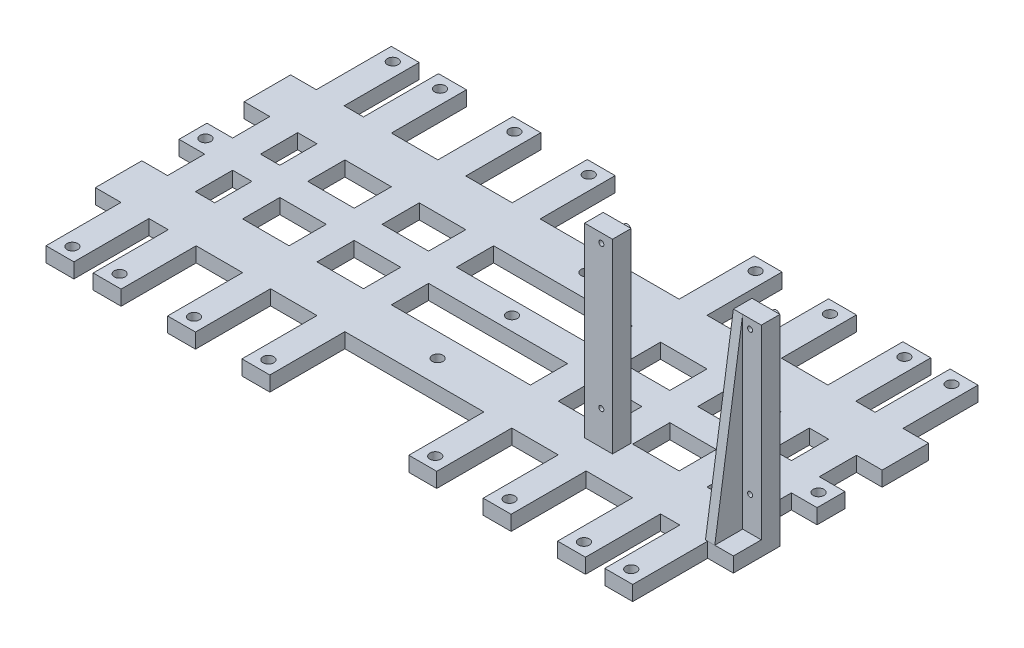
SolidWorks part; units mm, degrees
ref_plane "Front Plane" through (0, 0, 0) normal (0, 0, 1) x (1, 0, 0)
ref_plane "Top Plane" through (0, 0, 0) normal (0, 1, 0) x (1, 0, 0)
ref_plane "Right Plane" through (0, 0, 0) normal (1, 0, 0) x (0, 0, -1)
sketch "Sketch1" plane through (0, 0, 0) normal (0, 1, 0) x (1, 0, 0)
  line L0 (-157.74, 40.34) -> (-157.74, 145.9098) construction
  line L1 (0, 0) -> (-15, 0)
  line L2 (0, 0) -> (0, 185.68)
  line L3 (0, 92.84) -> (-15, 92.84)
  line L4 (-15, 0) -> (-15, 185.68)
  line L5 (-25.39, 92.84) -> (-40.39, 92.84)
  line L6 (-25.39, 185.68) -> (-25.39, 0)
  line L7 (-25.39, 0) -> (-40.39, 0)
  line L8 (-40.39, 185.68) -> (-40.39, 0)
  line L9 (-65.38, 92.84) -> (-80.38, 92.84)
  line L10 (-65.38, 185.68) -> (-65.38, 0)
  line L11 (-65.38, 0) -> (-80.38, 0)
  line L12 (-80.38, 185.68) -> (-80.38, 0)
  line L13 (-105.37, 92.84) -> (-120.37, 92.84)
  line L14 (-105.37, 185.68) -> (-105.37, 0)
  line L15 (-105.37, 0) -> (-120.37, 0)
  line L16 (-120.37, 185.68) -> (-120.37, 0)
  line L17 (13.8, 40.34) -> (-329.28, 40.34)
  line L18 (13.8, 40.34) -> (13.8, 65.34)
  line L19 (13.8, 65.34) -> (-329.28, 65.34)
  line L20 (-157.74, 40.34) -> (-157.74, 65.34)
  line L25 (0, 92.84) -> (-189.9909, 92.84) construction
  line L26 (13.8, 100.34) -> (-329.28, 100.34)
  line L27 (13.8, 85.34) -> (-329.28, 85.34)
  line L28 (13.8, 85.34) -> (13.8, 100.34)
  line L29 (13.8, 92.84) -> (-329.28, 92.84)
  line L30 (-157.74, 85.34) -> (-157.74, 100.34)
  line L31 (13.8, 120.34) -> (-329.28, 120.34)
  line L32 (-157.74, 145.34) -> (-157.74, 120.34)
  line L33 (13.8, 145.34) -> (-329.28, 145.34)
  line L34 (13.8, 145.34) -> (13.8, 120.34)
  line L35 (0, 185.68) -> (-15, 185.68)
  line L36 (-25.39, 185.68) -> (-40.39, 185.68)
  line L37 (-65.38, 185.68) -> (-80.38, 185.68)
  line L38 (-105.37, 185.68) -> (-120.37, 185.68)
  line L39 (-210.11, 185.68) -> (-195.11, 185.68)
  line L40 (-250.1, 185.68) -> (-235.1, 185.68)
  line L41 (-290.09, 185.68) -> (-275.09, 185.68)
  line L42 (-315.48, 185.68) -> (-300.48, 185.68)
  line L43 (-329.28, 145.34) -> (-329.28, 120.34)
  line L44 (-329.28, 85.34) -> (-329.28, 100.34)
  line L45 (-329.28, 40.34) -> (-329.28, 65.34)
  line L46 (-195.11, 185.68) -> (-195.11, 0)
  line L47 (-210.11, 0) -> (-195.11, 0)
  line L48 (-210.11, 185.68) -> (-210.11, 0)
  line L49 (-210.11, 92.84) -> (-195.11, 92.84)
  line L50 (-235.1, 185.68) -> (-235.1, 0)
  line L51 (-250.1, 0) -> (-235.1, 0)
  line L52 (-250.1, 185.68) -> (-250.1, 0)
  line L53 (-250.1, 92.84) -> (-235.1, 92.84)
  line L54 (-275.09, 185.68) -> (-275.09, 0)
  line L55 (-290.09, 0) -> (-275.09, 0)
  line L56 (-290.09, 185.68) -> (-290.09, 0)
  line L57 (-290.09, 92.84) -> (-275.09, 92.84)
  line L58 (-300.48, 0) -> (-300.48, 185.68)
  line L59 (-315.48, 92.84) -> (-300.48, 92.84)
  line L60 (-315.48, 0) -> (-315.48, 185.68)
  line L61 (-315.48, 0) -> (-300.48, 0)
  circle A0 centre (-7.5, 6.7) radius 2.895
  circle A1 centre (-32.89, 6.7) radius 2.895
  circle A2 centre (-72.88, 6.7) radius 2.895
  circle A3 centre (-112.87, 6.7) radius 2.895
  circle A4 centre (7.1, 52.84) radius 2.895 construction
  circle A5 centre (7.1, 92.84) radius 2.895
  circle A6 centre (-157.74, 92.84) radius 2.895
  circle A7 centre (-157.74, 52.84) radius 2.895
  circle A8 centre (-157.74, 132.84) radius 2.895
  circle A9 centre (7.1, 132.84) radius 2.895 construction
  circle A10 centre (-72.88, 178.98) radius 2.895
  circle A11 centre (-32.89, 178.98) radius 2.895
  circle A12 centre (-7.5, 178.98) radius 2.895
  circle A13 centre (-112.87, 178.98) radius 2.895
  circle A14 centre (-202.61, 178.98) radius 2.895
  circle A15 centre (-307.98, 178.98) radius 2.895
  circle A16 centre (-282.59, 178.98) radius 2.895
  circle A17 centre (-242.6, 178.98) radius 2.895
  circle A18 centre (-322.58, 132.84) radius 2.895 construction
  circle A19 centre (-322.58, 92.84) radius 2.895
  circle A20 centre (-322.58, 52.84) radius 2.895 construction
  circle A21 centre (-202.61, 6.7) radius 2.895
  circle A22 centre (-242.6, 6.7) radius 2.895
  circle A23 centre (-282.59, 6.7) radius 2.895
  circle A24 centre (-307.98, 6.7) radius 2.895
  point P19 (-7.5, 0)
  point P26 (-32.89, 0)
  point P27 (-72.88, 0)
  point P28 (-112.87, 0)
  point P41 (13.8, 52.84)
  dimension "D4" = 5.79
  dimension "D2" = 15
  dimension "D3" = 6.7
  dimension "D5" = 25.39
  dimension "D6" = 39.99
  dimension "D7" = 39.99
  dimension "D8" = 21.3
  dimension "D9" = 25
  dimension "D10" = 14.6
  dimension "D11" = 46.14
  dimension "D12" = 40
  dimension "D13" = 44.87
  dimension "D14" = 7.5
extrude "Boss-Extrude1" add sketch "Sketch1" along normal blind 8 contours L17 L56 L55 L54 A23 | L19 L56 L17 L54 | L60 L61 L58 L17 A24 | L58 L17 L56 L19 | L60 L17 L58 L19 | L17 L60 L19 L45 A20 | L60 L19 L58 L27 | L60 L29 L58 L26 | L60 L27 L58 L29 | L29 L56 L27 L54 | L58 L27 L56 L29 | L58 L29 L56 L26 | L29 A19 L60 L26 L44 | L29 A19 L44 L27 L60 | L29 L54 L27 L52 | L26 L54 L29 L52 | L26 L56 L29 L54 | L27 L56 L19 L54 | L19 L54 L17 L52 | L19 L52 L17 L50 | L17 L52 L51 L50 A22 | L27 L52 L19 L50 | L29 L52 L27 L50 | L26 L52 L29 L50 | L19 L50 L17 L48 | L17 L48 L47 L46 A21 | L19 L48 L17 L46 | A7 L20 L19 L46 L17 | L27 L48 L19 L46 | L29 L48 L27 L46 | L29 L50 L27 L48 | L26 L50 L29 L48 | L26 L48 L29 L46 | L60 L26 L58 L31 | L60 L31 L58 L33 | L31 L60 L33 L43 A18 | A6 L30 L26 L46 L29 | A6 L29 L46 L27 L30 | A6 L30 L27 L16 L29 | A6 L29 L16 L26 L30 | L14 L26 L16 L13 | L27 L14 L13 L16 | L14 L27 L16 L19 | A7 L20 L17 L16 L19 | L14 L19 L16 L17 | L14 L31 L16 L26 | L31 L48 L26 L46 | L31 L52 L26 L50 | L31 L56 L26 L54 | L14 L17 L16 L15 A3 | L12 L19 L14 L17 | L10 L19 L12 L17 | L10 L17 L12 L11 A2 | L10 L27 L12 L19 | L8 L19 L10 L17 | L6 L17 L8 L7 A1 | L6 L19 L8 L17 | L4 L19 L6 L17 | L2 L19 L4 L17 | L2 L17 L4 L1 A0 | L18 L19 L2 L17 A4 | L2 L27 L4 L19 | L6 L27 L8 L19 | L6 L26 L8 L5 | L27 L6 L5 L8 | L4 L29 L6 L27 | L29 L4 L26 L6 | L27 L2 L3 L4 | L2 L26 L4 L3 | A5 L29 L28 L26 L2 | A5 L29 L2 L27 L28 | L8 L29 L10 L27 | L29 L8 L26 L10 | L27 L10 L9 L12 | L10 L26 L12 L9 | L12 L29 L14 L27 | L29 L12 L26 L14 | L10 L31 L12 L26 | L6 L31 L8 L26 | L2 L31 L4 L26 | L2 L35 L4 L33 A12 | L6 L36 L8 L33 A11 | L10 L37 L12 L33 A10 | L14 L38 L16 L33 A13 | L39 L48 L33 L46 A14 | L40 L52 L33 L50 A17 | L41 L56 L33 L54 A16 | L60 L33 L58 L42 A15 | L32 A8 L33 L46 L31 | L32 A8 L31 L16 L33 | L14 L33 L16 L31 | L12 L33 L14 L31 | L10 L33 L12 L31 | L8 L33 L10 L31 | L6 L33 L8 L31 | L4 L33 L6 L31 | L2 L33 L4 L31 | L34 L33 L2 L31 A9 | L33 L48 L31 L46 | L33 L50 L31 L48 | L58 L31 L56 L33 | L33 L56 L31 L54 | L33 L54 L31 L52 | L33 L52 L31 L50
sketch "Sketch2" plane through (0, 8, 0) normal (0, 1, 0) x (1, 0, 0)
  line L0 (13.8, 65.34) -> (0, 65.34) construction
  line L1 (13.8, 65.34) -> (-1.2, 65.34)
  line L2 (13.8, 65.34) -> (13.8, 55.34)
  line L3 (13.8, 55.34) -> (-1.2, 55.34)
  line L4 (-1.2, 65.34) -> (-1.2, 55.34)
  line L5 (-81.2, 65.34) -> (-66.2, 65.34)
  line L6 (-81.2, 65.34) -> (-81.2, 55.34)
  line L7 (-81.2, 55.34) -> (-66.2, 55.34)
  line L8 (-66.2, 65.34) -> (-66.2, 55.34)
  line L9 (13.8, 40.34) -> (13.8, 65.34) construction
  dimension "D1" = 15
  dimension "D2" = 95
  dimension "D3" = 10
extrude "Boss-Extrude2" add sketch "Sketch2" along normal blind 100
sketch "Sketch3" plane through (0, 0, -65.34) normal (0, 0, -1) x (-1, 0, 0)
  line L0 (-13.8, 108) -> (1.2, 108) construction
  line L2 (-13.8, 108) -> (-13.8, 0) construction
  circle A4 centre (-7.8, 103.1) radius 2
  circle A5 centre (-7.8, 26.15) radius 2
  circle A6 centre (72.2, 26.15) radius 2
  circle A7 centre (72.2, 103.1) radius 2
  point P5 (0, 0)
  point P7 (0, 0)
  dimension "D2" = 76.95
  dimension "D3" = 4
  dimension "D1" = 4.9
  dimension "D4" = 6
  dimension "D5" = 80
extrude "Boss-Extrude3" add sketch "Sketch3" along normal blind 4
sketch "Sketch5" plane through (0, 0, -69.34) normal (0, 0, -1) x (-1, 0, 0)
  circle A0 centre (-7.8, 103.1) radius 1.35
  circle A1 centre (-7.8, 26.15) radius 1.35
  circle A2 centre (72.2, 26.15) radius 1.35
  circle A3 centre (72.2, 103.1) radius 1.35
  dimension "D1" = 2.7
extrude "Cut-Extrude1" cut sketch "Sketch5" against normal up to next
sketch "Sketch7" plane through (-1.2, 0, 0) normal (-1, 0, 0) x (0, 0, 1)
  line L0 (-40.34, 8) -> (-55.34, 108)
  line L1 (-55.34, 8) -> (-40.34, 8)
  line L2 (-55.34, 108) -> (-55.34, 8)
extrude "Boss-Extrude4" add sketch "Sketch7" against normal blind 5
